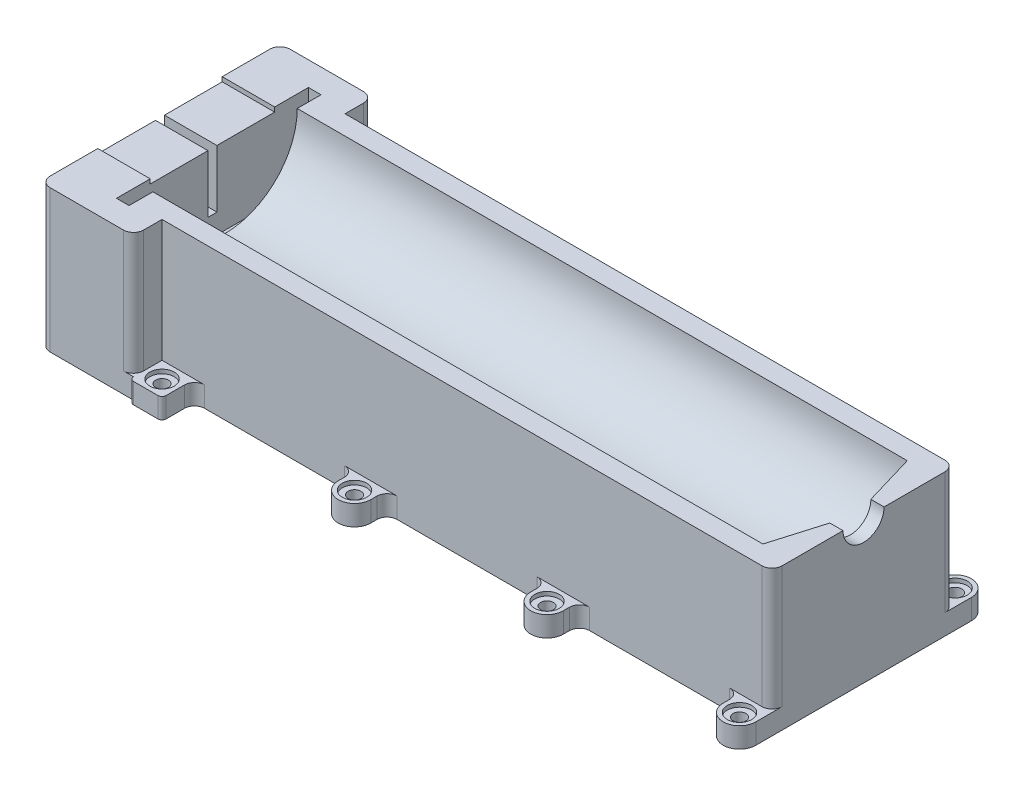
SolidWorks part; units mm, degrees
ref_plane "Front Plane" through (0, 0, 0) normal (0, 0, 1) x (1, 0, 0)
ref_plane "Top Plane" through (0, 0, 0) normal (0, 1, 0) x (1, 0, 0)
ref_plane "Right Plane" through (0, 0, 0) normal (1, 0, 0) x (0, 0, -1)
sketch "Sketch2" plane through (0, 0, 0) normal (0, 1, 0) x (1, 0, 0)
  line L1 (0, 0) -> (-166, 0)
  line L2 (0, 0) -> (0, -45)
  line L3 (0, -45) -> (-166, -45)
  line L4 (-166, 0) -> (-166, -45)
  dimension "D1" = 45
  dimension "D2" = 166
extrude "Boss-Extrude1" add sketch "Sketch2" along normal blind 35
sketch "Sketch3" plane through (0, 35, 0) normal (0, 1, 0) x (1, 0, 0)
  line L0 (-166, -22.5) -> (0, -22.5) construction
  line L1 (-166, 0) -> (-166, -45) construction
  line L2 (0, -45) -> (0, 0) construction
  line L3 (-7, -4.75) -> (-3.25, -17.45)
  line L4 (-157, -22.5) -> (-7, -22.5)
  line L5 (-157, -22.5) -> (-157, -4.75)
  line L6 (-157, -4.75) -> (-7, -4.75)
  line L7 (-7, -22.5) -> (-7, -4.75)
  line L8 (-3.25, -22.5) -> (3.5, -22.5)
  line L9 (-3.25, -22.5) -> (-3.25, -17.45)
  line L10 (-3.25, -17.45) -> (3.5, -17.45)
  line L11 (3.5, -22.5) -> (3.5, -17.45)
  line L12 (-7, -22.5) -> (-3.25, -22.5)
  point P18 (3.5, -19.975)
  dimension "D1" = 5.05
  dimension "D2" = 17.75
  dimension "D3" = 160.5
  dimension "D4" = 6.75
  dimension "D5" = 150
  dimension "D6" = 3.5
revolve "Cut-Revolve1" cut sketch "Sketch3" angle 360 about L0
sketch "Sketch6" plane through (0, 0, 0) normal (0, -1, 0) x (1, 0, 0)
  line L8 (-150, 45) -> (-150, 52)
  line L17 (-166, 45) -> (0, 45) construction
  line L18 (-150, 52) -> (-173, 52)
  line L19 (-173, 52) -> (-173, -7)
  line L20 (-173, -7) -> (-150, -7)
  line L21 (-150, -7) -> (-150, 0)
  line L22 (0, 0) -> (-166, 0) construction
  line L23 (-150, 0) -> (-166, 0)
  line L24 (-166, 0) -> (-166, 45)
  line L25 (-166, 45) -> (-150, 45)
  line L26 (-157, 4.75) -> (-157, 40.25) construction
  dimension "D1" = 7
  dimension "D2" = 7
  dimension "D3" = 7
extrude "Boss-Extrude4" add sketch "Sketch6" against normal blind 35
sketch "Sketch8" plane through (0, 35, 0) normal (0, 1, 0) x (1, 0, 0)
  line L0 (-157, -40.25) -> (-157, -4.75) construction
  line L1 (-160.1, 1.1) -> (-157, 1.1)
  line L2 (-160.1, 1.1) -> (-160.1, -46.1)
  line L3 (-160.1, -46.1) -> (-157, -46.1)
  line L4 (-157, 1.1) -> (-157, -46.1)
  line L5 (-173, -52) -> (-173, 7) construction
  point P6 (-160.1, -22.5)
  point P9 (-173, -22.5)
  dimension "D1" = 0
  dimension "D2" = 47.2
  dimension "D3" = 3.1
  dimension "D4" = 90
extrude "Cut-Extrude2" cut sketch "Sketch8" against normal blind 20.15
sketch "Sketch9" plane through (-173, 0, 0) normal (-1, 0, 0) x (0, 0, 1)
  line L1 (52, 35) -> (-7, 35) construction
  line L2 (21.4, 50.3) -> (23.6, 50.3)
  line L3 (21.4, 50.3) -> (21.4, 19.7)
  line L4 (21.4, 19.7) -> (23.6, 19.7)
  line L5 (23.6, 50.3) -> (23.6, 19.7)
  line L6 (7.2, 36.1) -> (37.8, 36.1)
  line L7 (7.2, 36.1) -> (7.2, 33.9)
  line L8 (7.2, 33.9) -> (37.8, 33.9)
  line L9 (37.8, 36.1) -> (37.8, 33.9)
  point P8 (22.5, 50.3)
  point P9 (22.5, 36.1)
  point P10 (37.8, 35)
  point P11 (23.6, 35)
  point P14 (22.5, 35)
  line M3 (52, 35) -> (-7, 35)
  dimension "D1" = 30.6
  dimension "D2" = 2.2
extrude "Cut-Extrude4" cut sketch "Sketch9" against normal blind 20.15 contours L3 L6 L5 L2 | L7 L8 L3 M3 | L3 L8 L5 M3 | L9 L5 L8 M3 | L9 L6 L5 M3 | L6 L7 L3 M3 | L6 L3 L5 M3 | L8 L3 L4 L5
sketch "Sketch11" plane through (0, 0, 0) normal (0, -1, 0) x (-1, 0, 0)
  line L0 (150, 7) -> (150, 0) construction
  line L1 (143, -53) -> (149, -53)
  line L2 (142, -52) -> (142, 7)
  line L3 (143, 8) -> (149, 8)
  line L4 (150, -52) -> (150, 7)
  line L5 (98.6667, -49) -> (98.6667, 4) construction
  line L6 (94.6667, -49) -> (94.6667, 4)
  line L7 (102.6667, -49) -> (102.6667, 4)
  line L8 (4, -49) -> (4, 4) construction
  line L9 (0, -49) -> (0, 4)
  line L10 (8, -49) -> (8, 4)
  line L12 (150, -45) -> (0, -45) construction
  line L13 (0, -45) -> (0, 0) construction
  line L14 (51.3333, -49) -> (51.3333, 4) construction
  line L15 (47.3333, -49) -> (47.3333, 4)
  line L16 (55.3333, -49) -> (55.3333, 4)
  line L17 (0, 0) -> (150, 0) construction
  line L18 (142, 0) -> (102.6667, 0)
  line L20 (94.6667, 0) -> (55.3333, 0)
  line L21 (47.3333, 0) -> (8, 0)
  line L22 (8, -45) -> (47.3333, -45)
  line L23 (55.3333, -45) -> (94.6667, -45)
  line L24 (102.6667, -45) -> (142, -45)
  arc A0 (94.6667, -49) -> (102.6667, -49) centre (98.6667, -49) ccw
  arc A1 (102.6667, 4) -> (94.6667, 4) centre (98.6667, 4) ccw
  arc A2 (0, -49) -> (8, -49) centre (4, -49) ccw
  arc A3 (8, 4) -> (0, 4) centre (4, 4) ccw
  circle A4 centre (98.6667, -49) radius 1.575
  circle A6 centre (146, -49) radius 1.575
  circle A7 centre (146, -49) radius 3
  circle A8 centre (4, -49) radius 1.575
  arc A9 (47.3333, -49) -> (55.3333, -49) centre (51.3333, -49) ccw
  arc A10 (55.3333, 4) -> (47.3333, 4) centre (51.3333, 4) ccw
  circle A11 centre (51.3333, -49) radius 1.575
  circle A12 centre (146, 4) radius 1.65
  circle A13 centre (98.6667, 4) radius 1.65
  circle A14 centre (51.3333, 4) radius 1.65
  circle A15 centre (4, 4) radius 1.65
  arc A16 (142, 7) -> (143, 8) centre (143, 7) cw
  arc A17 (149, 8) -> (150, 7) centre (149, 7) cw
  arc A18 (143, -53) -> (142, -52) centre (143, -52) cw
  arc A19 (149, -53) -> (150, -52) centre (149, -52) ccw
  circle A20 centre (105.1667, 2.5) radius 2.5
  circle A21 centre (139.5, 2.5) radius 2.5
  circle A22 centre (92.1667, 2.5) radius 2.5
  circle A23 centre (57.8333, 2.5) radius 2.5
  circle A24 centre (44.8333, 2.5) radius 2.5
  circle A25 centre (10.5, 2.5) radius 2.5
  circle A26 centre (10.5, -47.5) radius 2.5
  circle A27 centre (44.8333, -47.5) radius 2.5
  circle A28 centre (57.8333, -47.5) radius 2.5
  circle A29 centre (92.1667, -47.5) radius 2.5
  circle A30 centre (105.1667, -47.5) radius 2.5
  circle A31 centre (139.5, -47.5) radius 2.5
  point P8 (98.6667, -22.5)
  point P13 (4, -22.5)
  point P35 (51.3333, -22.5)
  point P58 (150, 8)
  line M49 (0, -45) -> (150, -45)
  line M50 (150, -45) -> (150, -52)
  line M54 (150, 7) -> (150, 0)
  line M55 (150, 0) -> (0, 0)
  dimension "D1" = 6
  dimension "D2" = 3.15
  dimension "D12" = 3.3
  dimension "D15" = 1
  dimension "D16" = 1
  dimension "D17" = 5
  dimension "D3" = 4
  dimension "D4" = 4
  dimension "D5" = 4
  dimension "D6" = 4
  dimension "D7" = 4
  dimension "D8" = 4
  dimension "D9" = 4
  dimension "D10" = 47.3333
  dimension "D11" = 47.3333
  dimension "D13" = 4
  dimension "D14" = 4
extrude "Boss-Extrude5" add sketch "Sketch11" against normal blind 5 contours L1 A19 L2 A18 A7 M50 M49 | A7 A6 | A31 L2 M49 | A30 L7 M49 | L6 A0 L7 A4 M49 | A29 L6 M49 | A28 L16 M49 | L15 A9 L16 A11 M49 | A27 L15 M49 | A26 L10 M49 | L9 A2 L10 A8 M49 | L10 A3 L9 A15 M55 | A25 L10 M55 | A24 L15 M55 | L16 A10 L15 A14 M55 | A23 L16 M55 | A22 L6 M55 | L7 A1 L6 A13 M55 | A20 L7 L18 | A17 L3 A16 L2 A12 M55 M54 | A21 L2 M55
sketch "Sketch12" plane through (0, 5, 0) normal (0, 1, 0) x (1, 0, 0)
  circle A0 centre (-146, 4) radius 3
  circle A1 centre (-98.6667, 4) radius 3
  circle A2 centre (-51.3333, 4) radius 3
  circle A3 centre (-4, 4) radius 3
  circle A4 centre (-4, -49) radius 3
  circle A5 centre (-51.3333, -49) radius 3
  circle A6 centre (-98.6667, -49) radius 3
  circle A7 centre (-146, -49) radius 3
  dimension "D1" = 6
extrude "Cut-Extrude6" cut sketch "Sketch12" against normal blind 1
fillet "Fillet1" radius 2.5 6 edges at (0, 20, 45) (0, 20, 0) (-150, 20, -7) (-173, 17.5, -7) (-173, 17.5, 52) (-150, 20, 52)
